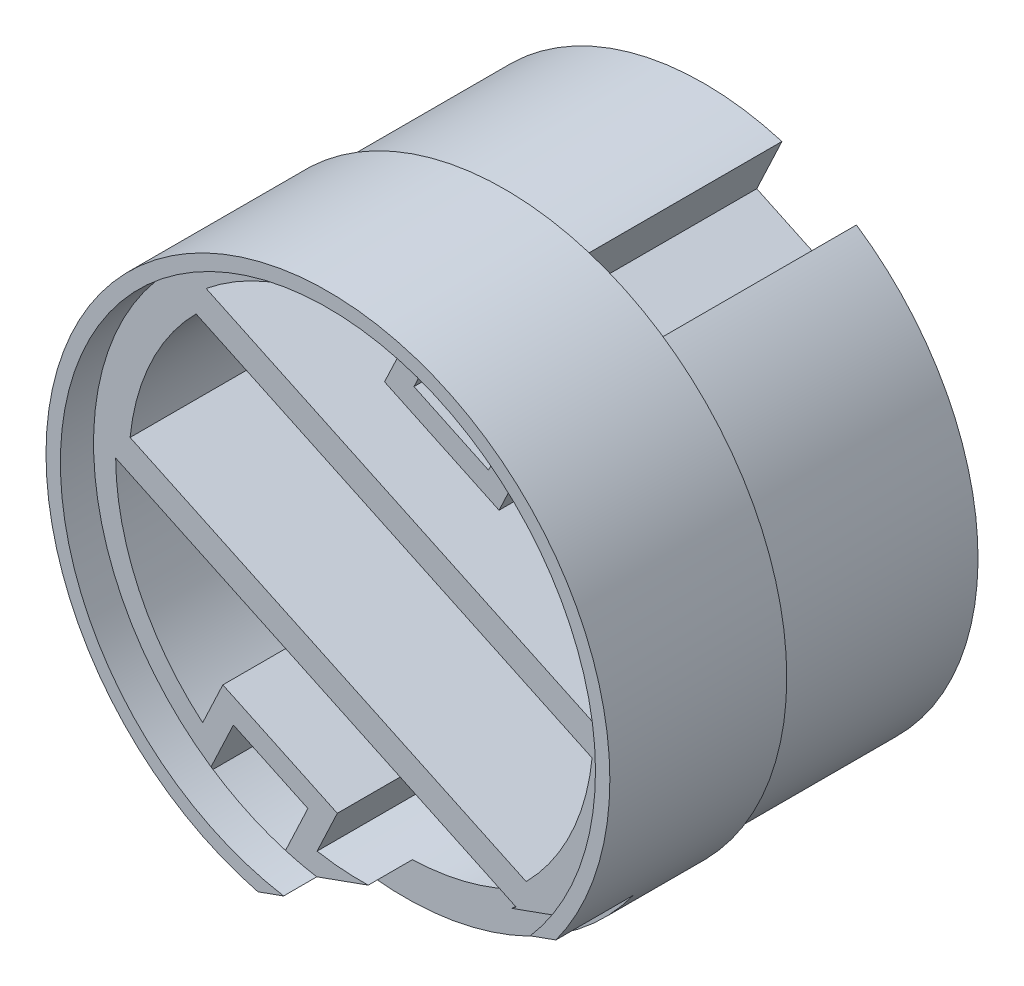
SolidWorks part; units mm, degrees
ref_plane "前视基准面" through (0, 0, 0) normal (0, 0, 1) x (1, 0, 0)
ref_plane "上视基准面" through (0, 0, 0) normal (0, 1, 0) x (1, 0, 0)
ref_plane "右视基准面" through (0, 0, 0) normal (1, 0, 0) x (0, 0, -1)
other "Configuration Table"
sketch "草图1" plane through (0, 0, 0) normal (0, 0, 1) x (1, 0, 0)
  circle A0 centre (0, 0) radius 12.4
  dimension "D1" = 24.8
extrude "凸台-拉伸1" add sketch "草图1" along normal blind 17
sketch "草图2" plane through (0, 0, 17) normal (0, 0, 1) x (1, 0, 0)
  circle A0 centre (0, 0) radius 12.1
  dimension "D1" = 24.2
extrude "切除-拉伸1" cut sketch "草图2" against normal blind 1.5
sketch "草图3" plane through (0, 0, 15.5) normal (0, 0, 1) x (1, 0, 0)
  line L1 (-4.0975, -8.6609) -> (-6.3953, -7.5784) construction
  line L2 (-6.9155, -10.2925) -> (-5.7746, -7.8708)
  line L4 (-1.7997, -9.7434) -> (-4.0975, -8.6609) construction
  line L5 (-5.7746, -7.8708) -> (-2.4057, -9.458)
  line L6 (-2.4057, -9.458) -> (-3.5476, -11.8817)
  line L7 (0, 0) -> (10.9461, -5.1568) construction
  line L8 (5.761, 7.8772) -> (6.9029, 10.301)
  line L9 (2.3922, 9.4643) -> (5.761, 7.8772)
  line L10 (3.5331, 11.886) -> (2.3922, 9.4643)
  circle A0 centre (0, 0) radius 12.4 construction
  arc A1 (-6.9155, -10.2925) -> (-3.5476, -11.8817) centre (0, 0) ccw
  circle A2 centre (0, 0) radius 12.1 construction
  arc A3 (3.5331, 11.886) -> (6.9029, 10.301) centre (0, 0) cw
extrude "切除-拉伸2" cut sketch "草图3" against normal through all
sketch "草图4" plane through (0, 0, 17) normal (0, 0, 1) x (1, 0, 0)
  circle A1 centre (0, 0) radius 12.75
  circle A2 centre (0, 0) radius 12.4 construction
  circle A3 centre (0, 0) radius 12.4
  dimension "D1" = 25.5
extrude "凸台-拉伸2" add sketch "草图4" against normal blind 8
sketch "草图5" plane through (0, 0, 15.5) normal (0, 0, 1) x (1, 0, 0)
  line L0 (-7.4638, 7.3852) -> (10.4471, -1.0528)
  line L1 (2.3922, 9.4643) -> (5.761, 7.8772) construction
  line L2 (0, 0) -> (9.4987, -4.4749) construction
  line L3 (-10.4471, 1.0528) -> (7.4638, -7.3852)
  arc A0 (-7.4638, 7.3852) -> (-10.4471, 1.0528) centre (0, 0) ccw
  arc A1 (7.4638, -7.3852) -> (10.4471, -1.0528) centre (0, 0) ccw
  dimension "D1" = 21
  dimension "D2" = 3.5
extrude "切除-拉伸3" cut sketch "草图5" against normal blind 14.5
sketch "草图6" plane through (0, 0, 15.5) normal (0, 0, 1) x (1, 0, 0)
  line L30 (11.0997, 0.0768) -> (-7.0084, 8.6077)
  line L31 (10.4471, -1.0528) -> (-7.4638, 7.3852) construction
  line L32 (0, 0) -> (9.4987, -4.4749) construction
  line L33 (7.0084, -8.6077) -> (-11.0997, -0.0768)
  line L36 (-7.1657, -8.4772) -> (-6.253, -6.54)
  line L37 (-6.253, -6.54) -> (-1.0749, -8.9795)
  line L38 (-1.0749, -8.9795) -> (-1.9892, -10.9203)
  line L39 (7.1538, 8.4872) -> (6.2395, 6.5464)
  line L40 (6.2395, 6.5464) -> (1.0614, 8.9859)
  line L41 (1.0614, 8.9859) -> (1.974, 10.9231)
  line L42 (-7.1657, -8.4772) -> (-6.253, -6.54)
  line L43 (-6.253, -6.54) -> (-1.0749, -8.9795)
  line L44 (-1.0749, -8.9795) -> (-1.9892, -10.9203)
  line L45 (7.1538, 8.4872) -> (6.2395, 6.5464)
  line L46 (6.2395, 6.5464) -> (1.0614, 8.9859)
  line L47 (1.0614, 8.9859) -> (1.974, 10.9231)
  arc A10 (7.4638, -7.3852) -> (10.4471, -1.0528) centre (0, 0) ccw construction
  arc A11 (11.0997, 0.0768) -> (7.1538, 8.4872) centre (0, 0) ccw
  arc A12 (-1.9892, -10.9203) -> (7.1538, 8.4872) centre (0, 0) ccw
  arc A13 (1.974, 10.9231) -> (-7.1657, -8.4772) centre (0, 0) ccw
  arc A14 (-1.9892, -10.9203) -> (7.0084, -8.6077) centre (0, 0) ccw
  arc A15 (1.974, 10.9231) -> (-7.0084, 8.6077) centre (0, 0) ccw
  arc A16 (-11.0997, -0.0768) -> (-7.1657, -8.4772) centre (0, 0) ccw
  dimension "D2" = 4.8
  dimension "D1" = 1
extrude "切除-拉伸4" cut sketch "草图6" against normal through all
sketch "草图7" plane through (0, 0, 17) normal (0, 0, 1) x (1, 0, 0)
  line L0 (-3.1647, -12.351) -> (10.3109, -7.4998)
  circle A2 centre (0, 0) radius 12.75 construction
  arc A3 (-3.1647, -12.351) -> (10.3109, -7.4998) centre (0, 0) ccw
  point P6 (-3.1001, -12.3277)
extrude "切除-拉伸5" cut sketch "草图7" against normal blind 3.5
